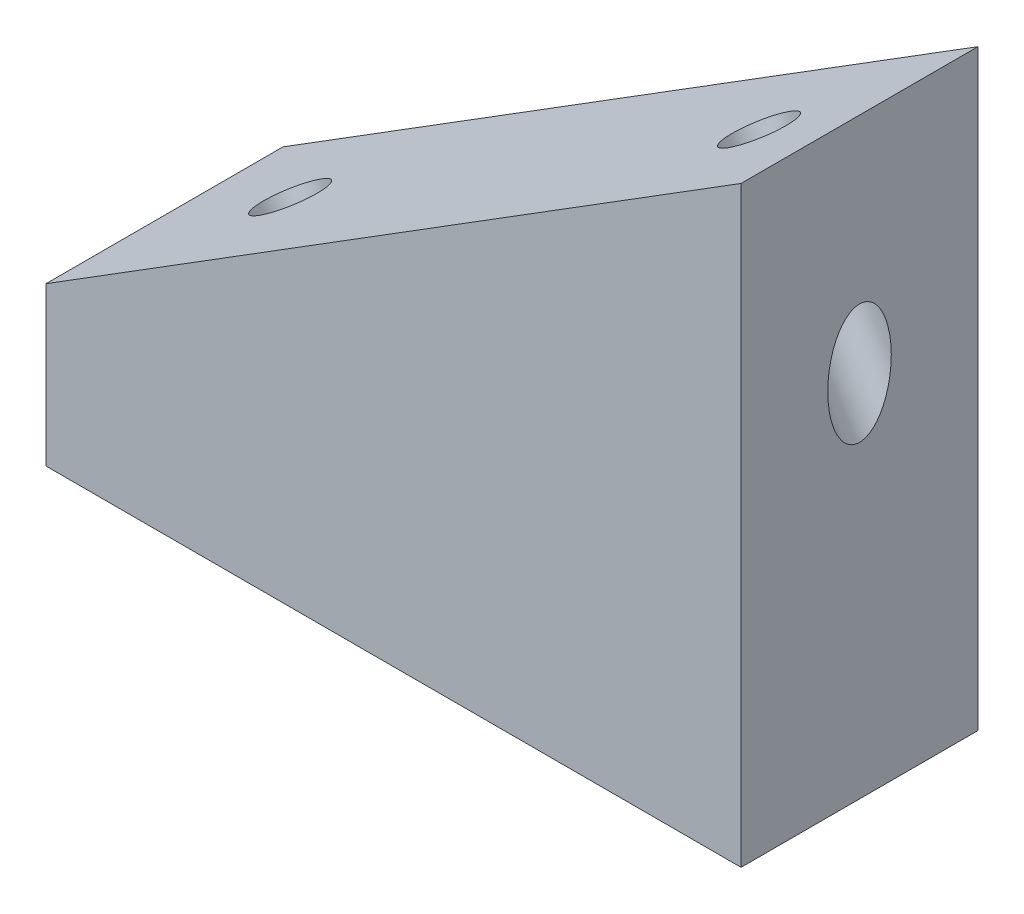
SolidWorks part; units mm, degrees
ref_plane "Front Plane" through (0, 0, 0) normal (0, 0, 1) x (1, 0, 0)
ref_plane "Top Plane" through (0, 0, 0) normal (0, 1, 0) x (1, 0, 0)
ref_plane "Right Plane" through (0, 0, 0) normal (1, 0, 0) x (0, 0, -1)
sketch "Sketch2" plane through (0, 0, 0) normal (0, 0, 1) x (1, 0, 0)
  line L1 (0, 47.6177) -> (-55.88, 12.7)
  line L3 (-55.88, 12.7) -> (-55.88, 0)
  line L4 (-55.88, 0) -> (0, 0)
  line L5 (0, 0) -> (0, 47.6177)
  point P0 (0, 0)
  dimension "D1" = 32
  dimension "D2" = 12.7
  dimension "D3" = 55.88
extrude "Boss-Extrude1" add sketch "Sketch2" along normal blind 19.05
sketch "Sketch3" plane through (-21.3993, 34.246, 0) normal (-0.5299, 0.848, 0) x (0.848, 0.5299, 0)
  line L0 (25.2335, -9.525) -> (-40.659, -9.525) construction
  line L3 (-28.7415, 0) -> (-28.7415, -19.05) construction
  line L4 (25.2335, 0) -> (-40.659, 0) construction
  line L5 (25.2335, -19.05) -> (-40.659, -19.05) construction
  line L6 (25.2335, -19.05) -> (25.2335, 0) construction
  line L7 (15.7085, 0) -> (15.7085, -19.05) construction
  line L8 (-40.659, -19.05) -> (-40.659, 0) construction
  point P2 (0, 0)
  point P3 (0, 0)
  point P4 (0, 0)
  point P12 (0, 0)
  point P15 (0, 0)
  dimension "D1" = 44.45
  dimension "D2" = 9.525
hole_wizard "#7 (0.201) Diameter Hole1" positions "Sketch4" profile "Sketch5" hole size "#7" standard "ANSI Inch"
sketch "Sketch4" plane through (-21.3993, 34.246, 0) normal (-0.5299, 0.848, 0) x (0.848, 0.5299, 0)
  line L0 (-28.7415, 0) -> (-28.7415, -19.05) construction
  line L1 (15.7085, 0) -> (15.7085, -19.05) construction
  point P0 (-28.7415, -9.525)
  point P4 (15.7085, -9.525)
sketch "Sketch5" plane through (-45.7734, 19.0153, 9.525) normal (0, 0, 1) x (-0.848, -0.5299, 0)
  line L0 (0, 0) -> (0, 25.4)
  line L1 (0, 25.4) -> (2.5527, 25.4)
  line L2 (2.5527, 25.4) -> (2.5527, 0)
  line L5 (2.5527, 0) -> (0, 0)
  line L10 (0, 25.4) -> (-2.5527, 25.4) construction
  line L11 (0, -6.35) -> (0, 107.95) construction
  dimension "Hole Dia." = 5.1054
  dimension "Hole Depth" = 25.4
  dimension "Drill Angle" = 180
